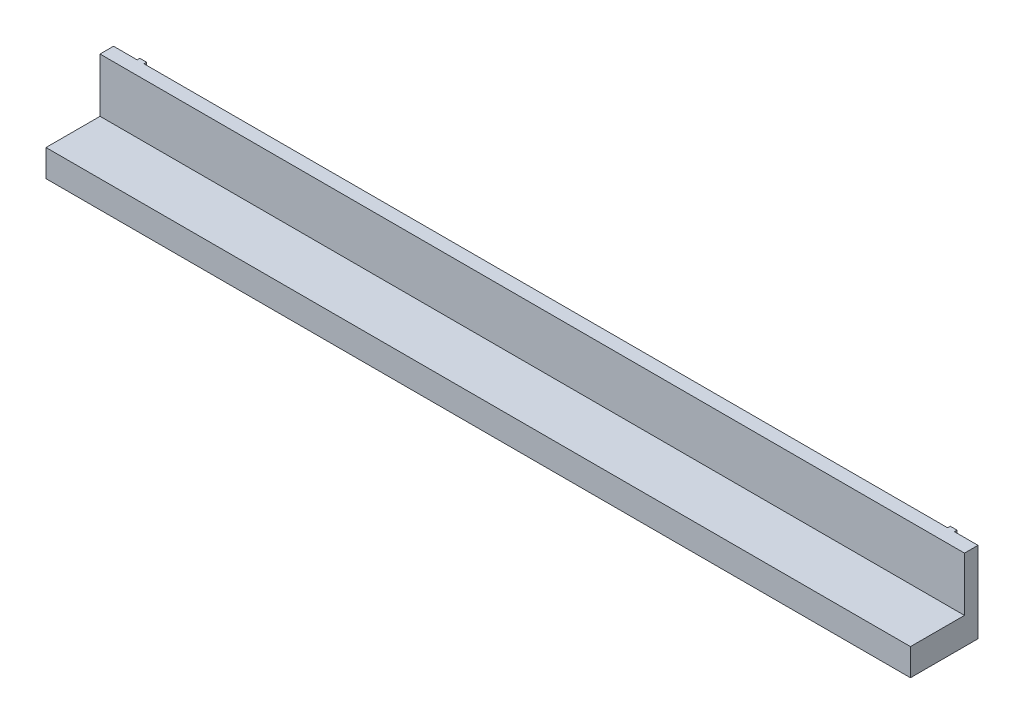
SolidWorks part; units mm, degrees
ref_plane "Front Plane" through (0, 0, 0) normal (0, 0, 1) x (1, 0, 0)
ref_plane "Top Plane" through (0, 0, 0) normal (0, 1, 0) x (1, 0, 0)
ref_plane "Right Plane" through (0, 0, 0) normal (1, 0, 0) x (0, 0, -1)
sketch "Sketch1" plane through (0, 0, 0) normal (0, 0, 1) x (1, 0, 0)
  line L0 (0, 0) -> (812.8, 0)
  line L1 (812.8, 0) -> (812.8, 76.1149)
  line L2 (812.8, 76.1149) -> (0, 76.1149)
  line L3 (0, 76.1149) -> (0, 0)
  dimension "D1" = 812.8
extrude "Boss-Extrude1" add sketch "Sketch1" along normal blind 12.7
sketch "Sketch2" plane through (0, 0, 0) normal (0, -1, 0) x (1, 0, 0)
  line L0 (0, 12.7) -> (0, 63.5)
  line L1 (0, 63.5) -> (812.8, 63.5)
  line L2 (812.8, 63.5) -> (812.8, 12.7)
  line L7 (0, 0) -> (812.8, 0)
  line L8 (812.8, 0) -> (812.8, 12.7)
  line L9 (812.8, 12.7) -> (0, 12.7)
  line L10 (0, 12.7) -> (0, 0)
  line L11 (0, 0) -> (812.8, 0)
  line L12 (812.8, 0) -> (812.8, 12.7)
  line L14 (0, 12.7) -> (0, 0)
  dimension "D1" = 50.8
  dimension "D2" = 0
extrude "Boss-Extrude2" add sketch "Sketch2" against normal blind 25.4
sketch "Sketch3" plane through (0, 0, 0) normal (0, 0, -1) x (-1, 0, 0)
  line L0 (-406.4, 76.1149) -> (-406.4, 0) construction
  line L1 (-812.8, 76.1149) -> (0, 76.1149) construction
  line L2 (0, 0) -> (-812.8, 0) construction
  line L3 (-790.575, 76.1149) -> (-790.575, 0)
  line L4 (-784.225, 76.1149) -> (-784.225, 0)
  line L5 (-790.575, 76.1149) -> (-784.225, 76.1149)
  line L6 (-790.575, 0) -> (-784.225, 0)
  line L7 (-22.225, 76.1149) -> (-28.575, 76.1149)
  line L8 (-22.225, 76.1149) -> (-22.225, 0)
  line L9 (-28.575, 76.1149) -> (-28.575, 0)
  line L10 (-22.225, 0) -> (-28.575, 0)
  dimension "D1" = 384.175
  dimension "D2" = 6.35
extrude "Boss-Extrude4" add sketch "Sketch3" along normal blind 2.54
